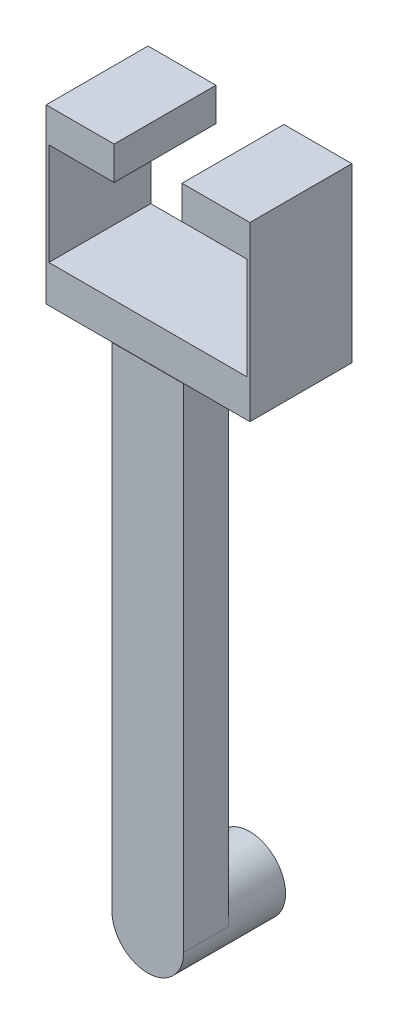
SolidWorks part; units mm, degrees
material "6061-T6 (SS)"
ref_plane "Front Plane" through (0, 0, 0) normal (0, 0, 1) x (1, 0, 0)
ref_plane "Top Plane" through (0, 0, 0) normal (0, 1, 0) x (1, 0, 0)
ref_plane "Right Plane" through (0, 0, 0) normal (1, 0, 0) x (0, 0, -1)
sketch "Sketch2" plane through (0, 0, 0) normal (0, 0, 1) x (1, 0, 0)
  circle A0 centre (0, 0) radius 13.4112
  dimension "D1" = 26.8224
extrude "Boss-Extrude1" add sketch "Sketch2" along normal blind 38.1
sketch "Sketch5" plane through (0, 0, 38.1) normal (0, 0, 1) x (1, 0, 0)
  line L1 (-13.4112, 0) -> (13.4112, 0)
  line L2 (-13.4112, 0) -> (-13.4112, 184.15)
  line L3 (-13.4112, 184.15) -> (13.4112, 184.15)
  line L4 (13.4112, 0) -> (13.4112, 184.15)
  circle A0 centre (0, 0) radius 13.4112 construction
  dimension "D1" = 26.8224
  dimension "D2" = 184.15
extrude "Boss-Extrude2" add sketch "Sketch5" against normal blind 16.7386
sketch "Sketch8" plane through (0, 184.15, 0) normal (0, 1, 0) x (1, 0, 0)
  line L1 (-38.1, 0.1018) -> (38.1, 0.1018)
  line L3 (-38.1, 0.1018) -> (-38.1, -37.9982)
  line L4 (-38.1, -37.9982) -> (38.1, -37.9982)
  line L5 (38.1, 0.1018) -> (38.1, -37.9982)
  dimension "D1" = 38.1
  dimension "D2" = 76.2
extrude "Boss-Extrude3" add sketch "Sketch8" along normal blind 13.97
sketch "Sketch9" plane through (0, 198.12, 0) normal (0, 1, 0) x (1, 0, 0)
  line L0 (-38.1, -37.9982) -> (38.1, -37.9982) construction
  line L1 (-38.1, 0.1018) -> (-37.084, 0.1018)
  line L2 (-38.1, 0.1018) -> (-38.1, -37.9982)
  line L3 (-38.1, -37.9982) -> (-37.084, -37.9982)
  line L4 (-37.084, 0.1018) -> (-37.084, -37.9982)
  line L6 (38.1, 0.1018) -> (37.084, 0.1018)
  line L7 (38.1, 0.1018) -> (38.1, -37.9982)
  line L8 (38.1, -37.9982) -> (37.084, -37.9982)
  line L9 (37.084, 0.1018) -> (37.084, -37.9982)
  dimension "D1" = 1.016
  dimension "D2" = 1.016
extrude "Boss-Extrude4" add sketch "Sketch9" along normal blind 38.1
sketch "Sketch10" plane through (0, 236.22, 0) normal (0, 1, 0) x (1, 0, 0)
  line L0 (-37.084, -37.9982) -> (37.084, -37.9982) construction
  line L1 (-38.1, 0.1018) -> (-12.7, 0.1018)
  line L2 (-38.1, 0.1018) -> (-38.1, -37.9982)
  line L3 (-38.1, -37.9982) -> (-12.7, -37.9982)
  line L4 (-12.7, 0.1018) -> (-12.7, -37.9982)
  line L6 (38.1, 0.1018) -> (12.7, 0.1018)
  line L7 (38.1, 0.1018) -> (38.1, -37.9982)
  line L8 (38.1, -37.9982) -> (12.7, -37.9982)
  line L9 (12.7, 0.1018) -> (12.7, -37.9982)
  dimension "D1" = 25.4
  dimension "D2" = 25.4
extrude "Boss-Extrude5" add sketch "Sketch10" along normal blind 12.446
equation "\"F\"= 600"
equation "\"Sy\"= 40000"
equation "\"E\"= 10000000"
equation "\"Defmax\"= 0.005in"
equation "\"a\"= 0.498in"
equation "\"b\"= 0.9992in"
equation "\"c\"= 1.499in"
equation "\"d\"= 2.4964in"
equation "\"rA\"= 0.528in"
equation "\"aB\"= 0.696in"
equation "\"tB\"= ( ( 1200 * 7.25 * 4 ) / ( \"E\" * \"Defmax\" ) ) / 1.15"
equation "\"hC\"= 0.5473in"
equation "\"LC\"= 2.4964in"
equation "\"WC\"= 1.5in"
equation "\"aD\"= 0.06in"
equation "\"DL\"= ( ( 600 / 1000 ) / \"WD\" )"
equation "\"WD\"= 1.499in"
equation "\"eH\"= 0.4897in"
equation "\"LE\"= 0.9992in"
equation "\"WE\"= 1.50in"
equation "\"D1@Sketch2\"= \"rA\" * 2"
equation "\"LA\"= 1.5in"
